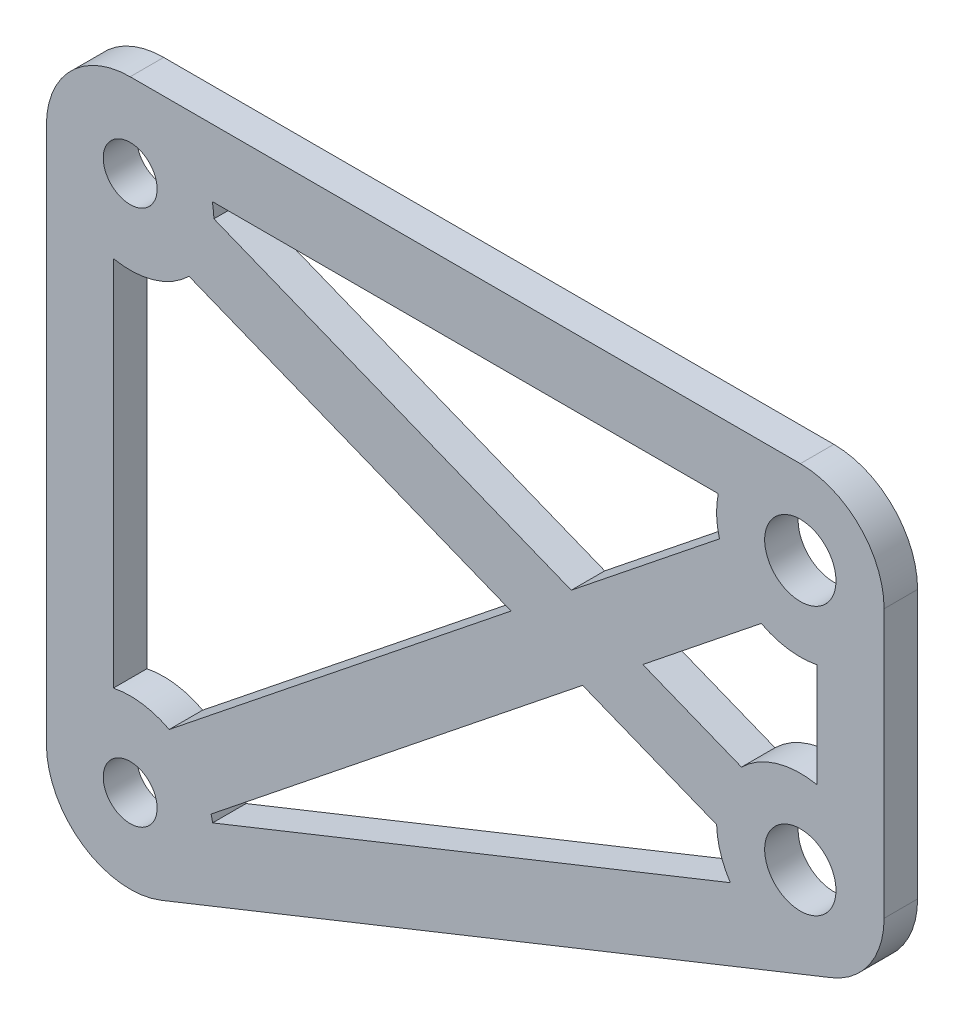
SolidWorks part; units mm, degrees
ref_plane "Front Plane" through (0, 0, 0) normal (0, 0, 1) x (1, 0, 0)
ref_plane "Top Plane" through (0, 0, 0) normal (0, 1, 0) x (1, 0, 0)
ref_plane "Right Plane" through (0, 0, 0) normal (1, 0, 0) x (0, 0, -1)
sketch "Sketch1" plane through (0, 0, 0) normal (0, 0, 1) x (1, 0, 0)
  line L0 (0, 50.8) -> (0, 0) construction
  line L1 (0, 0) -> (63.5, 25.4) construction
  line L2 (63.5, 25.4) -> (63.5, 50.8) construction
  line L3 (63.5, 50.8) -> (0, 50.8) construction
  line L4 (0, 58.7375) -> (63.5, 58.7375)
  line L5 (71.4375, 50.8) -> (71.4375, 25.4)
  line L6 (66.4479, 18.0302) -> (2.9479, -7.3698)
  line L7 (-7.9375, 0) -> (-7.9375, 50.8)
  arc A0 (-7.9375, 0) -> (2.9479, -7.3698) centre (0, 0) ccw
  arc A1 (0, 58.7375) -> (-7.9375, 50.8) centre (0, 50.8) ccw
  arc A2 (71.4375, 50.8) -> (63.5, 58.7375) centre (63.5, 50.8) ccw
  arc A3 (66.4479, 18.0302) -> (71.4375, 25.4) centre (63.5, 25.4) ccw
  dimension "D1" = 15.875
  dimension "D2" = 50.8
  dimension "D3" = 63.5
  dimension "D4" = 25.4
extrude "Boss-Extrude1" add sketch "Sketch1" along normal blind 3.175
hole_wizard "1/4 Clearance Hole1" positions "Sketch2" profile "Sketch3" hole size "1/4" standard "ANSI Inch" end condition through all
sketch "Sketch2" plane through (0, 0, 3.175) normal (0, 0, 1) x (1, 0, 0)
  point P0 (63.5, 50.8)
  point P3 (63.5, 25.4)
sketch "Sketch3" plane through (63.5, 50.8, 3.175) normal (1, 0, 0) x (0, -1, 0)
  line L0 (0, 0) -> (0, 3.175)
  line L1 (0, 3.175) -> (3.3782, 3.175)
  line L2 (3.3782, 3.175) -> (3.3782, 0)
  line L5 (3.3782, 0) -> (0, 0)
  line L11 (0, -6.35) -> (0, 107.95) construction
  dimension "Thru Hole Dia." = 6.7564
  dimension "Thru Hole Depth" = 3.175
hole_wizard "#10 Clearance Hole1" positions "Sketch4" profile "Sketch5" hole size "#10" standard "ANSI Inch" end condition through all
sketch "Sketch4" plane through (0, 0, 3.175) normal (0, 0, 1) x (1, 0, 0)
  point P0 (0, 50.8)
  point P3 (0, 0)
sketch "Sketch5" plane through (0, 50.8, 3.175) normal (1, 0, 0) x (0, -1, 0)
  line L0 (0, 0) -> (0, 3.175)
  line L1 (0, 3.175) -> (2.5527, 3.175)
  line L2 (2.5527, 3.175) -> (2.5527, 0)
  line L5 (2.5527, 0) -> (0, 0)
  line L11 (0, -6.35) -> (0, 107.95) construction
  dimension "Thru Hole Dia." = 5.1054
  dimension "Thru Hole Depth" = 3.175
sketch "Sketch6" plane through (0, 0, 3.175) normal (0, 0, 1) x (1, 0, 0)
  line L0 (0, 50.8) -> (63.5, 25.4) construction
  line L1 (63.5, 50.8) -> (0, 0) construction
  line L2 (-1.1792, 47.8521) -> (62.3208, 22.4521)
  line L3 (61.5166, 53.2793) -> (-1.9834, 2.4793)
  line L4 (1.1792, 53.7479) -> (64.6792, 28.3479)
  line L5 (65.4834, 48.3207) -> (1.9834, -2.4793)
  line L14 (63.5, 52.3875) -> (0, 52.3875)
  line L15 (-1.5875, 50.8) -> (-1.5875, 0)
  line L16 (0.5896, -1.474) -> (64.0896, 23.926)
  line L17 (65.0875, 25.4) -> (65.0875, 50.8)
  line L18 (63.5, 52.3875) -> (0, 52.3875)
  line L19 (-1.5875, 50.8) -> (-1.5875, 0)
  line L20 (0.5896, -1.474) -> (64.0896, 23.926)
  line L21 (65.0875, 25.4) -> (65.0875, 50.8)
  circle A0 centre (0, 50.8) radius 7.9375
  arc A1 (0, 58.7375) -> (-7.9375, 50.8) centre (0, 50.8) ccw construction
  circle A2 centre (63.5, 50.8) radius 7.9375
  arc A3 (71.4375, 50.8) -> (63.5, 58.7375) centre (63.5, 50.8) ccw construction
  circle A4 centre (63.5, 25.4) radius 7.9375
  arc A5 (66.4479, 18.0302) -> (71.4375, 25.4) centre (63.5, 25.4) ccw construction
  circle A6 centre (0, 0) radius 7.9375
  arc A7 (-7.9375, 0) -> (2.9479, -7.3698) centre (0, 0) ccw construction
  arc A16 (65.0875, 50.8) -> (63.5, 52.3875) centre (63.5, 50.8) ccw
  arc A17 (0, 52.3875) -> (-1.5875, 50.8) centre (0, 50.8) ccw
  arc A18 (-1.5875, 0) -> (0.5896, -1.474) centre (0, 0) ccw
  arc A19 (64.0896, 23.926) -> (65.0875, 25.4) centre (63.5, 25.4) ccw
  arc A20 (65.0875, 50.8) -> (63.5, 52.3875) centre (63.5, 50.8) ccw
  arc A21 (0, 52.3875) -> (-1.5875, 50.8) centre (0, 50.8) ccw
  arc A22 (-1.5875, 0) -> (0.5896, -1.474) centre (0, 0) ccw
  arc A23 (64.0896, 23.926) -> (65.0875, 25.4) centre (63.5, 25.4) ccw
  dimension "D1" = 3.175
  dimension "D2" = 3.175
  dimension "D3" = 6.35
extrude "Cut-Extrude1" cut sketch "Sketch6" against normal through all contours A6 L3 L2 A0 L19 | A2 L18 A0 L4 L3 | A4 L21 A2 L5 L4 | A6 L20 A4 L2 L5
